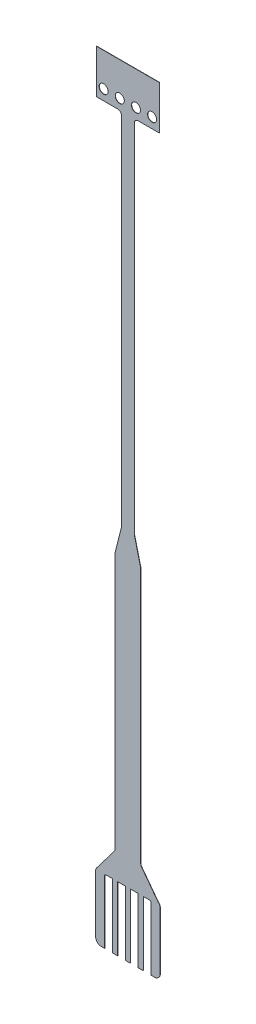
SolidWorks part; units mm, degrees
ref_plane "Front Plane" through (0, 0, 0) normal (0, 0, 1) x (1, 0, 0)
ref_plane "Top Plane" through (0, 0, 0) normal (0, 1, 0) x (1, 0, 0)
ref_plane "Right Plane" through (0, 0, 0) normal (1, 0, 0) x (0, 0, -1)
sketch "Model" plane through (0, 0, 0) normal (0, 0, 1) x (1, 0, 0)
  line L0 (-1.25, -28.292) -> (-1.2492, -28.3022)
  line L1 (-1.2492, -28.3022) -> (-1.2483, -28.3122)
  line L2 (-1.2483, -28.3122) -> (-1.2465, -28.3223)
  line L3 (-1.2465, -28.3223) -> (-1.2445, -28.332)
  line L4 (-1.2445, -28.332) -> (-1.242, -28.3417)
  line L5 (-1.242, -28.3417) -> (-1.239, -28.3515)
  line L6 (-1.239, -28.3515) -> (-1.2355, -28.361)
  line L7 (-1.2355, -28.361) -> (-1.2317, -28.3702)
  line L8 (-1.2317, -28.3702) -> (-1.2272, -28.3795)
  line L9 (-1.2272, -28.3795) -> (-1.2225, -28.3885)
  line L10 (-1.2225, -28.3885) -> (-1.2175, -28.397)
  line L11 (-1.2175, -28.397) -> (-1.2117, -28.4055)
  line L12 (-1.2117, -28.4055) -> (-1.206, -28.4135)
  line L13 (-1.206, -28.4135) -> (-1.1995, -28.4215)
  line L14 (-1.1995, -28.4215) -> (-1.1927, -28.429)
  line L15 (-1.1927, -28.429) -> (-1.1857, -28.4363)
  line L16 (-1.1857, -28.4363) -> (-1.1783, -28.443)
  line L17 (-1.1783, -28.443) -> (-1.1705, -28.4495)
  line L18 (-1.1705, -28.4495) -> (-1.1625, -28.4557)
  line L19 (-1.1625, -28.4557) -> (-1.1542, -28.4615)
  line L20 (-1.1542, -28.4615) -> (-1.1457, -28.4667)
  line L21 (-1.1457, -28.4667) -> (-1.137, -28.4717)
  line L22 (-1.137, -28.4717) -> (-1.1277, -28.4762)
  line L23 (-1.1277, -28.4762) -> (-1.1185, -28.4802)
  line L24 (-1.1185, -28.4802) -> (-1.1093, -28.484)
  line L25 (-1.1093, -28.484) -> (-1.0995, -28.4872)
  line L26 (-1.0995, -28.4872) -> (-1.09, -28.4897)
  line L27 (-1.09, -28.4897) -> (-1.08, -28.492)
  line L28 (-1.08, -28.492) -> (-1.07, -28.494)
  line L29 (-1.07, -28.494) -> (-1.06, -28.4952)
  line L30 (-1.06, -28.4952) -> (-1.05, -28.496)
  line L31 (-1.05, -28.496) -> (-0.9, -28.496)
  line L32 (-0.9, -28.496) -> (-0.9, -26.0412)
  line L33 (-0.9, -26.0412) -> (-0.8992, -26.0365)
  line L34 (-0.8992, -26.0365) -> (-0.8982, -26.0317)
  line L35 (-0.8982, -26.0317) -> (-0.8965, -26.027)
  line L36 (-0.8965, -26.027) -> (-0.8942, -26.0227)
  line L37 (-0.8942, -26.0227) -> (-0.8917, -26.0185)
  line L38 (-0.8917, -26.0185) -> (-0.889, -26.0145)
  line L39 (-0.889, -26.0145) -> (-0.8857, -26.0107)
  line L40 (-0.8857, -26.0107) -> (-0.882, -26.0075)
  line L41 (-0.882, -26.0075) -> (-0.878, -26.0048)
  line L42 (-0.878, -26.0048) -> (-0.8737, -26.0022)
  line L43 (-0.8737, -26.0022) -> (-0.8695, -26)
  line L44 (-0.8695, -26) -> (-0.8647, -25.9982)
  line L45 (-0.8647, -25.9982) -> (-0.86, -25.9973)
  line L46 (-0.86, -25.9973) -> (-0.8552, -25.9965)
  line L47 (-0.8552, -25.9965) -> (-0.8502, -25.9962)
  line L48 (-0.8502, -25.9962) -> (-0.8502, -25.996)
  line L49 (-0.8502, -25.996) -> (-0.605, -25.996)
  line L50 (-0.605, -25.996) -> (-0.6035, -25.9962)
  line L51 (-0.6035, -25.9962) -> (-0.602, -25.997)
  line L52 (-0.602, -25.997) -> (-0.601, -25.998)
  line L53 (-0.601, -25.998) -> (-0.6002, -25.9995)
  line L54 (-0.6002, -25.9995) -> (-0.6, -26.001)
  line L55 (-0.6, -26.001) -> (-0.6, -28.496)
  line L56 (-0.6, -28.496) -> (-0.4, -28.496)
  line L57 (-0.4, -28.496) -> (-0.4, -26.001)
  line L58 (-0.4, -26.001) -> (-0.3997, -25.9995)
  line L59 (-0.3997, -25.9995) -> (-0.399, -25.998)
  line L60 (-0.399, -25.998) -> (-0.398, -25.997)
  line L61 (-0.398, -25.997) -> (-0.3965, -25.9962)
  line L62 (-0.3965, -25.9962) -> (-0.395, -25.996)
  line L63 (-0.395, -25.996) -> (-0.105, -25.996)
  line L64 (-0.105, -25.996) -> (-0.1035, -25.9962)
  line L65 (-0.1035, -25.9962) -> (-0.102, -25.997)
  line L66 (-0.102, -25.997) -> (-0.101, -25.998)
  line L67 (-0.101, -25.998) -> (-0.1002, -25.9995)
  line L68 (-0.1002, -25.9995) -> (-0.1, -26.001)
  line L69 (-0.1, -26.001) -> (-0.1, -28.496)
  line L70 (-0.1, -28.496) -> (0.1, -28.496)
  line L71 (0.1, -28.496) -> (0.1, -26.001)
  line L72 (0.1, -26.001) -> (0.1002, -25.9995)
  line L73 (0.1002, -25.9995) -> (0.101, -25.998)
  line L74 (0.101, -25.998) -> (0.102, -25.997)
  line L75 (0.102, -25.997) -> (0.1035, -25.9962)
  line L76 (0.1035, -25.9962) -> (0.105, -25.996)
  line L77 (0.105, -25.996) -> (0.395, -25.996)
  line L78 (0.395, -25.996) -> (0.3965, -25.9962)
  line L79 (0.3965, -25.9962) -> (0.398, -25.997)
  line L80 (0.398, -25.997) -> (0.399, -25.998)
  line L81 (0.399, -25.998) -> (0.3997, -25.9995)
  line L82 (0.3997, -25.9995) -> (0.4, -26.001)
  line L83 (0.4, -26.001) -> (0.4, -28.496)
  line L84 (0.4, -28.496) -> (0.6, -28.496)
  line L85 (0.6, -28.496) -> (0.6, -26.001)
  line L86 (0.6, -26.001) -> (0.6002, -25.9995)
  line L87 (0.6002, -25.9995) -> (0.601, -25.998)
  line L88 (0.601, -25.998) -> (0.602, -25.997)
  line L89 (0.602, -25.997) -> (0.6035, -25.9962)
  line L90 (0.6035, -25.9962) -> (0.605, -25.996)
  line L91 (0.605, -25.996) -> (0.85, -25.996)
  line L92 (0.85, -25.996) -> (0.855, -25.9962)
  line L93 (0.855, -25.9962) -> (0.8597, -25.997)
  line L94 (0.8597, -25.997) -> (0.8645, -25.998)
  line L95 (0.8645, -25.998) -> (0.8692, -25.9997)
  line L96 (0.8692, -25.9997) -> (0.8735, -26.002)
  line L97 (0.8735, -26.002) -> (0.8777, -26.0045)
  line L98 (0.8777, -26.0045) -> (0.8817, -26.0072)
  line L99 (0.8817, -26.0072) -> (0.8855, -26.0105)
  line L100 (0.8855, -26.0105) -> (0.8888, -26.0143)
  line L101 (0.8888, -26.0143) -> (0.8915, -26.0182)
  line L102 (0.8915, -26.0182) -> (0.894, -26.0225)
  line L103 (0.894, -26.0225) -> (0.8962, -26.0267)
  line L104 (0.8962, -26.0267) -> (0.898, -26.0315)
  line L105 (0.898, -26.0315) -> (0.899, -26.0362)
  line L106 (0.899, -26.0362) -> (0.8997, -26.041)
  line L107 (0.8997, -26.041) -> (0.9, -26.046)
  line L108 (0.9, -26.046) -> (0.9, -28.496)
  line L109 (0.9, -28.496) -> (1.05, -28.496)
  line L110 (1.05, -28.496) -> (1.06, -28.4952)
  line L111 (1.06, -28.4952) -> (1.07, -28.494)
  line L112 (1.07, -28.494) -> (1.08, -28.492)
  line L113 (1.08, -28.492) -> (1.0897, -28.4897)
  line L114 (1.0897, -28.4897) -> (1.0995, -28.4872)
  line L115 (1.0995, -28.4872) -> (1.1093, -28.484)
  line L116 (1.1093, -28.484) -> (1.1185, -28.4802)
  line L117 (1.1185, -28.4802) -> (1.1277, -28.4762)
  line L118 (1.1277, -28.4762) -> (1.137, -28.4717)
  line L119 (1.137, -28.4717) -> (1.1457, -28.4667)
  line L120 (1.1457, -28.4667) -> (1.1542, -28.4615)
  line L121 (1.1542, -28.4615) -> (1.1625, -28.4557)
  line L122 (1.1625, -28.4557) -> (1.1705, -28.4495)
  line L123 (1.1705, -28.4495) -> (1.1783, -28.443)
  line L124 (1.1783, -28.443) -> (1.1857, -28.4363)
  line L125 (1.1857, -28.4363) -> (1.1927, -28.429)
  line L126 (1.1927, -28.429) -> (1.1995, -28.4215)
  line L127 (1.1995, -28.4215) -> (1.206, -28.4137)
  line L128 (1.206, -28.4137) -> (1.2117, -28.4055)
  line L129 (1.2117, -28.4055) -> (1.2175, -28.397)
  line L130 (1.2175, -28.397) -> (1.2225, -28.3885)
  line L131 (1.2225, -28.3885) -> (1.2272, -28.3795)
  line L132 (1.2272, -28.3795) -> (1.2317, -28.3702)
  line L133 (1.2317, -28.3702) -> (1.2355, -28.361)
  line L134 (1.2355, -28.361) -> (1.239, -28.3515)
  line L135 (1.239, -28.3515) -> (1.242, -28.3417)
  line L136 (1.242, -28.3417) -> (1.2445, -28.332)
  line L137 (1.2445, -28.332) -> (1.2465, -28.3223)
  line L138 (1.2465, -28.3223) -> (1.2483, -28.3122)
  line L139 (1.2483, -28.3122) -> (1.2492, -28.3022)
  line L140 (1.2492, -28.3022) -> (1.25, -28.292)
  line L141 (1.25, -28.292) -> (1.25, -26.046)
  line L142 (1.25, -26.046) -> (1.25, -26.045)
  line L143 (1.25, -26.045) -> (1.2497, -26.037)
  line L144 (1.2497, -26.037) -> (1.249, -26.028)
  line L145 (1.249, -26.028) -> (1.248, -26.019)
  line L146 (1.248, -26.019) -> (1.2462, -26.01)
  line L147 (1.2462, -26.01) -> (1.2442, -26.0012)
  line L148 (1.2442, -26.0012) -> (1.2417, -25.9925)
  line L149 (1.2417, -25.9925) -> (1.2388, -25.984)
  line L150 (1.2388, -25.984) -> (1.2352, -25.9757)
  line L151 (1.2352, -25.9757) -> (1.2315, -25.9675)
  line L152 (1.2315, -25.9675) -> (1.227, -25.9595)
  line L153 (1.227, -25.9595) -> (1.2225, -25.9518)
  line L154 (1.2225, -25.9518) -> (1.2172, -25.9443)
  line L155 (1.2172, -25.9443) -> (1.212, -25.937)
  line L156 (1.212, -25.937) -> (1.206, -25.93)
  line L157 (1.206, -25.93) -> (1.2, -25.9235)
  line L158 (1.2, -25.9235) -> (1.1935, -25.9172)
  line L159 (1.1935, -25.9172) -> (1.1865, -25.9112)
  line L160 (1.1865, -25.9112) -> (1.1863, -25.9111)
  line L161 (1.1863, -25.9111) -> (0.522, -25.0253)
  line L162 (0.522, -25.0253) -> (0.521, -25.0237)
  line L163 (0.521, -25.0237) -> (0.517, -25.0167)
  line L164 (0.517, -25.0167) -> (0.5135, -25.0095)
  line L165 (0.5135, -25.0095) -> (0.5102, -25.002)
  line L166 (0.5102, -25.002) -> (0.5075, -24.9945)
  line L167 (0.5075, -24.9945) -> (0.5052, -24.9867)
  line L168 (0.5052, -24.9867) -> (0.5032, -24.979)
  line L169 (0.5032, -24.979) -> (0.5018, -24.971)
  line L170 (0.5018, -24.971) -> (0.5008, -24.963)
  line L171 (0.5008, -24.963) -> (0.5, -24.955)
  line L172 (0.5, -24.955) -> (0.5, -14.996)
  line L173 (0.5, -14.996) -> (0.25, -13.996)
  line L174 (-0.25, -13.996) -> (-0.25, -0.15)
  line L175 (0.25, -13.996) -> (0.25, -0.15)
  line L177 (-0.25, -13.996) -> (-0.5, -14.996)
  line L178 (-0.5, -14.996) -> (-0.5, -24.948)
  line L179 (-0.5, -24.948) -> (-0.5002, -24.956)
  line L180 (-0.5002, -24.956) -> (-0.5008, -24.964)
  line L181 (-0.5008, -24.964) -> (-0.502, -24.972)
  line L182 (-0.502, -24.972) -> (-0.5035, -24.98)
  line L183 (-0.5035, -24.98) -> (-0.5052, -24.9877)
  line L184 (-0.5052, -24.9877) -> (-0.5077, -24.9955)
  line L185 (-0.5077, -24.9955) -> (-0.5105, -25.003)
  line L186 (-0.5105, -25.003) -> (-0.5135, -25.0105)
  line L187 (-0.5135, -25.0105) -> (-0.5172, -25.0177)
  line L188 (-0.5172, -25.0177) -> (-0.5196, -25.0221)
  line L189 (-0.5196, -25.0221) -> (-1.1864, -25.9113)
  line L190 (-1.1864, -25.9113) -> (-1.1867, -25.9115)
  line L191 (-1.1867, -25.9115) -> (-1.1935, -25.9175)
  line L192 (-1.1935, -25.9175) -> (-1.2, -25.9237)
  line L193 (-1.2, -25.9237) -> (-1.2062, -25.9302)
  line L194 (-1.2062, -25.9302) -> (-1.212, -25.9372)
  line L195 (-1.212, -25.9372) -> (-1.2175, -25.9445)
  line L196 (-1.2175, -25.9445) -> (-1.2225, -25.952)
  line L197 (-1.2225, -25.952) -> (-1.2272, -25.9597)
  line L198 (-1.2272, -25.9597) -> (-1.2315, -25.9677)
  line L199 (-1.2315, -25.9677) -> (-1.2352, -25.976)
  line L200 (-1.2352, -25.976) -> (-1.2388, -25.9842)
  line L201 (-1.2388, -25.9842) -> (-1.2417, -25.9927)
  line L202 (-1.2417, -25.9927) -> (-1.2442, -26.0015)
  line L203 (-1.2442, -26.0015) -> (-1.2462, -26.0102)
  line L204 (-1.2462, -26.0102) -> (-1.248, -26.0192)
  line L205 (-1.248, -26.0192) -> (-1.249, -26.0282)
  line L206 (-1.249, -26.0282) -> (-1.2497, -26.0372)
  line L207 (-1.2497, -26.0372) -> (-1.25, -26.0457)
  line L208 (-1.25, -26.0457) -> (-1.25, -26.046)
  line L209 (-1.25, -26.046) -> (-1.25, -28.292)
  line L210 (-1.225, 0) -> (-0.4, 0)
  line L211 (-0.4, 0) -> (-0.3915, -0.0003)
  line L212 (-0.3915, -0.0003) -> (-0.3832, -0.001)
  line L213 (-0.3832, -0.001) -> (-0.3747, -0.002)
  line L214 (-0.3747, -0.002) -> (-0.3665, -0.0037)
  line L215 (-0.3665, -0.0037) -> (-0.3585, -0.0057)
  line L216 (-0.3585, -0.0057) -> (-0.3505, -0.0085)
  line L217 (-0.3505, -0.0085) -> (-0.3425, -0.0115)
  line L218 (-0.3425, -0.0115) -> (-0.335, -0.0147)
  line L219 (-0.335, -0.0147) -> (-0.3275, -0.0187)
  line L220 (-0.3275, -0.0187) -> (-0.3202, -0.023)
  line L221 (-0.3202, -0.023) -> (-0.3132, -0.0278)
  line L222 (-0.3132, -0.0278) -> (-0.3065, -0.0327)
  line L223 (-0.3065, -0.0327) -> (-0.3, -0.0382)
  line L224 (-0.3, -0.0382) -> (-0.294, -0.044)
  line L225 (-0.294, -0.044) -> (-0.2883, -0.05)
  line L226 (-0.2883, -0.05) -> (-0.2827, -0.0565)
  line L227 (-0.2827, -0.0565) -> (-0.2777, -0.0632)
  line L228 (-0.2777, -0.0632) -> (-0.273, -0.0703)
  line L229 (-0.273, -0.0703) -> (-0.2687, -0.0775)
  line L230 (-0.2687, -0.0775) -> (-0.2647, -0.085)
  line L231 (-0.2647, -0.085) -> (-0.2615, -0.0925)
  line L232 (-0.2615, -0.0925) -> (-0.2585, -0.1005)
  line L233 (-0.2585, -0.1005) -> (-0.2558, -0.1085)
  line L234 (-0.2558, -0.1085) -> (-0.2538, -0.1165)
  line L235 (-0.2538, -0.1165) -> (-0.252, -0.1247)
  line L236 (-0.252, -0.1247) -> (-0.251, -0.1332)
  line L237 (-0.251, -0.1332) -> (-0.2502, -0.1415)
  line L238 (-0.2502, -0.1415) -> (-0.25, -0.15)
  line L239 (1.225, 0) -> (1.225, 1.7)
  line L276 (0.25, -0.15) -> (0.2502, -0.1415)
  line L277 (0.2502, -0.1415) -> (0.251, -0.1332)
  line L278 (0.251, -0.1332) -> (0.252, -0.1247)
  line L279 (0.252, -0.1247) -> (0.2538, -0.1165)
  line L280 (0.2538, -0.1165) -> (0.2558, -0.1085)
  line L281 (0.2558, -0.1085) -> (0.2585, -0.1005)
  line L282 (0.2585, -0.1005) -> (0.2615, -0.0925)
  line L283 (0.2615, -0.0925) -> (0.2647, -0.085)
  line L284 (0.2647, -0.085) -> (0.2687, -0.0775)
  line L285 (0.2687, -0.0775) -> (0.273, -0.0703)
  line L286 (0.273, -0.0703) -> (0.2777, -0.0632)
  line L287 (0.2777, -0.0632) -> (0.2827, -0.0565)
  line L288 (0.2827, -0.0565) -> (0.2883, -0.05)
  line L289 (0.2883, -0.05) -> (0.294, -0.044)
  line L290 (0.294, -0.044) -> (0.3, -0.0382)
  line L291 (0.3, -0.0382) -> (0.3065, -0.0327)
  line L292 (0.3065, -0.0327) -> (0.3132, -0.0278)
  line L293 (0.3132, -0.0278) -> (0.3202, -0.023)
  line L294 (0.3202, -0.023) -> (0.3275, -0.0187)
  line L295 (0.3275, -0.0187) -> (0.335, -0.0147)
  line L296 (0.335, -0.0147) -> (0.3425, -0.0115)
  line L297 (0.3425, -0.0115) -> (0.3505, -0.0085)
  line L298 (0.3505, -0.0085) -> (0.3585, -0.0057)
  line L299 (0.3585, -0.0057) -> (0.3665, -0.0037)
  line L300 (0.3665, -0.0037) -> (0.3747, -0.002)
  line L301 (0.3747, -0.002) -> (0.3832, -0.001)
  line L302 (0.3832, -0.001) -> (0.3915, -0.0003)
  line L303 (0.3915, -0.0003) -> (0.4, 0)
  line L304 (0.4, 0) -> (1.225, 0)
  line L442 (1.225, 1.7) -> (0.767, 1.7)
  line L444 (0.767, 0.4) -> (0.7672, 0.4068)
  line L445 (0.7672, 0.4068) -> (0.7675, 0.413)
  line L446 (0.7675, 0.413) -> (0.7682, 0.4197)
  line L447 (0.7682, 0.4197) -> (0.769, 0.4262)
  line L448 (0.769, 0.4262) -> (0.7702, 0.4327)
  line L449 (0.7702, 0.4327) -> (0.7715, 0.439)
  line L450 (0.7715, 0.439) -> (0.773, 0.4452)
  line L451 (0.773, 0.4452) -> (0.7747, 0.4515)
  line L452 (0.7747, 0.4515) -> (0.777, 0.458)
  line L453 (0.777, 0.458) -> (0.7792, 0.464)
  line L454 (0.7792, 0.464) -> (0.7818, 0.47)
  line L455 (0.7818, 0.47) -> (0.7843, 0.4758)
  line L456 (0.7843, 0.4758) -> (0.7875, 0.482)
  line L457 (0.7875, 0.482) -> (0.7905, 0.4875)
  line L458 (0.7905, 0.4875) -> (0.794, 0.4932)
  line L459 (0.794, 0.4932) -> (0.7975, 0.4985)
  line L460 (0.7975, 0.4985) -> (0.8013, 0.5037)
  line L461 (0.8013, 0.5037) -> (0.8053, 0.509)
  line L462 (0.8053, 0.509) -> (0.8092, 0.514)
  line L463 (0.8092, 0.514) -> (0.8137, 0.519)
  line L464 (0.8137, 0.519) -> (0.823, 0.5282)
  line L465 (0.823, 0.5282) -> (0.828, 0.5328)
  line L466 (0.828, 0.5328) -> (0.833, 0.5368)
  line L467 (0.833, 0.5368) -> (0.8382, 0.5407)
  line L468 (0.8382, 0.5407) -> (0.8435, 0.5445)
  line L469 (0.8435, 0.5445) -> (0.8488, 0.548)
  line L470 (0.8488, 0.548) -> (0.8545, 0.5515)
  line L471 (0.8545, 0.5515) -> (0.86, 0.5545)
  line L472 (0.86, 0.5545) -> (0.8662, 0.5577)
  line L473 (0.8662, 0.5577) -> (0.872, 0.5603)
  line L474 (0.872, 0.5603) -> (0.878, 0.5627)
  line L475 (0.878, 0.5627) -> (0.884, 0.565)
  line L476 (0.884, 0.565) -> (0.8905, 0.5672)
  line L477 (0.8905, 0.5672) -> (0.8967, 0.569)
  line L478 (0.8967, 0.569) -> (0.903, 0.5705)
  line L479 (0.903, 0.5705) -> (0.9093, 0.5717)
  line L480 (0.9093, 0.5717) -> (0.9157, 0.573)
  line L481 (0.9157, 0.573) -> (0.9223, 0.5737)
  line L482 (0.9223, 0.5737) -> (0.929, 0.5745)
  line L483 (0.929, 0.5745) -> (0.9353, 0.5747)
  line L484 (0.9353, 0.5747) -> (0.942, 0.575)
  line L485 (0.942, 0.575) -> (0.9487, 0.5747)
  line L486 (0.9487, 0.5747) -> (0.955, 0.5745)
  line L487 (0.955, 0.5745) -> (0.9617, 0.5737)
  line L488 (0.9617, 0.5737) -> (0.9682, 0.573)
  line L489 (0.9682, 0.573) -> (0.9747, 0.5717)
  line L490 (0.9747, 0.5717) -> (0.981, 0.5705)
  line L491 (0.981, 0.5705) -> (0.9873, 0.569)
  line L492 (0.9873, 0.569) -> (0.9935, 0.5672)
  line L493 (0.9935, 0.5672) -> (1, 0.565)
  line L494 (1, 0.565) -> (1.006, 0.5627)
  line L495 (1.006, 0.5627) -> (1.012, 0.5603)
  line L496 (1.012, 0.5603) -> (1.0177, 0.5577)
  line L497 (1.0177, 0.5577) -> (1.024, 0.5545)
  line L498 (1.024, 0.5545) -> (1.0295, 0.5515)
  line L499 (1.0295, 0.5515) -> (1.0353, 0.548)
  line L500 (1.0353, 0.548) -> (1.0405, 0.5445)
  line L501 (1.0405, 0.5445) -> (1.0457, 0.5407)
  line L502 (1.0457, 0.5407) -> (1.051, 0.5368)
  line L503 (1.051, 0.5368) -> (1.056, 0.5328)
  line L504 (1.056, 0.5328) -> (1.061, 0.5282)
  line L505 (1.061, 0.5282) -> (1.0702, 0.519)
  line L506 (1.0702, 0.519) -> (1.0747, 0.514)
  line L507 (1.0747, 0.514) -> (1.0787, 0.509)
  line L508 (1.0787, 0.509) -> (1.0827, 0.5037)
  line L509 (1.0827, 0.5037) -> (1.0865, 0.4985)
  line L510 (1.0865, 0.4985) -> (1.09, 0.4932)
  line L511 (1.09, 0.4932) -> (1.0935, 0.4875)
  line L512 (1.0935, 0.4875) -> (1.0965, 0.482)
  line L513 (1.0965, 0.482) -> (1.0998, 0.4758)
  line L514 (1.0998, 0.4758) -> (1.1022, 0.47)
  line L515 (1.1022, 0.47) -> (1.1048, 0.464)
  line L516 (1.1048, 0.464) -> (1.107, 0.458)
  line L517 (1.107, 0.458) -> (1.1093, 0.4515)
  line L518 (1.1093, 0.4515) -> (1.111, 0.4452)
  line L519 (1.111, 0.4452) -> (1.1125, 0.439)
  line L520 (1.1125, 0.439) -> (1.1138, 0.4327)
  line L521 (1.1138, 0.4327) -> (1.115, 0.4262)
  line L522 (1.115, 0.4262) -> (1.1158, 0.4197)
  line L523 (1.1158, 0.4197) -> (1.1165, 0.413)
  line L524 (1.1165, 0.413) -> (1.1167, 0.4068)
  line L525 (1.1167, 0.4068) -> (1.117, 0.4)
  line L526 (1.117, 0.4) -> (1.1167, 0.3932)
  line L527 (1.1167, 0.3932) -> (1.1165, 0.387)
  line L528 (1.1165, 0.387) -> (1.1158, 0.3802)
  line L529 (1.1158, 0.3802) -> (1.115, 0.3738)
  line L530 (1.115, 0.3738) -> (1.1138, 0.3673)
  line L531 (1.1138, 0.3673) -> (1.1125, 0.361)
  line L532 (1.1125, 0.361) -> (1.111, 0.3547)
  line L533 (1.111, 0.3547) -> (1.1093, 0.3485)
  line L534 (1.1093, 0.3485) -> (1.107, 0.342)
  line L535 (1.107, 0.342) -> (1.1048, 0.336)
  line L536 (1.1048, 0.336) -> (1.1022, 0.33)
  line L537 (1.1022, 0.33) -> (1.0998, 0.3242)
  line L538 (1.0998, 0.3242) -> (1.0965, 0.318)
  line L539 (1.0965, 0.318) -> (1.0935, 0.3125)
  line L540 (1.0935, 0.3125) -> (1.09, 0.3068)
  line L541 (1.09, 0.3068) -> (1.0865, 0.3015)
  line L542 (1.0865, 0.3015) -> (1.0827, 0.2962)
  line L543 (1.0827, 0.2962) -> (1.0787, 0.291)
  line L544 (1.0787, 0.291) -> (1.0747, 0.286)
  line L545 (1.0747, 0.286) -> (1.0702, 0.281)
  line L546 (1.0702, 0.281) -> (1.061, 0.2717)
  line L547 (1.061, 0.2717) -> (1.056, 0.2672)
  line L548 (1.056, 0.2672) -> (1.051, 0.2632)
  line L549 (1.051, 0.2632) -> (1.0457, 0.2592)
  line L550 (1.0457, 0.2592) -> (1.0405, 0.2555)
  line L551 (1.0405, 0.2555) -> (1.0353, 0.252)
  line L552 (1.0353, 0.252) -> (1.0295, 0.2485)
  line L553 (1.0295, 0.2485) -> (1.024, 0.2455)
  line L554 (1.024, 0.2455) -> (1.0177, 0.2422)
  line L555 (1.0177, 0.2422) -> (1.012, 0.2397)
  line L556 (1.012, 0.2397) -> (1.006, 0.2372)
  line L557 (1.006, 0.2372) -> (1, 0.235)
  line L558 (1, 0.235) -> (0.9935, 0.2327)
  line L559 (0.9935, 0.2327) -> (0.9873, 0.231)
  line L560 (0.9873, 0.231) -> (0.981, 0.2295)
  line L561 (0.981, 0.2295) -> (0.9747, 0.2282)
  line L562 (0.9747, 0.2282) -> (0.9682, 0.227)
  line L563 (0.9682, 0.227) -> (0.9617, 0.2263)
  line L564 (0.9617, 0.2263) -> (0.955, 0.2255)
  line L565 (0.955, 0.2255) -> (0.9487, 0.2253)
  line L566 (0.9487, 0.2253) -> (0.942, 0.225)
  line L567 (0.942, 0.225) -> (0.9353, 0.2253)
  line L568 (0.9353, 0.2253) -> (0.929, 0.2255)
  line L569 (0.929, 0.2255) -> (0.9223, 0.2263)
  line L570 (0.9223, 0.2263) -> (0.9157, 0.227)
  line L571 (0.9157, 0.227) -> (0.9093, 0.2282)
  line L572 (0.9093, 0.2282) -> (0.903, 0.2295)
  line L573 (0.903, 0.2295) -> (0.8967, 0.231)
  line L574 (0.8967, 0.231) -> (0.8905, 0.2327)
  line L575 (0.8905, 0.2327) -> (0.884, 0.235)
  line L576 (0.884, 0.235) -> (0.878, 0.2372)
  line L577 (0.878, 0.2372) -> (0.872, 0.2397)
  line L578 (0.872, 0.2397) -> (0.8662, 0.2422)
  line L579 (0.8662, 0.2422) -> (0.86, 0.2455)
  line L580 (0.86, 0.2455) -> (0.8545, 0.2485)
  line L581 (0.8545, 0.2485) -> (0.8488, 0.252)
  line L582 (0.8488, 0.252) -> (0.8435, 0.2555)
  line L583 (0.8435, 0.2555) -> (0.8382, 0.2592)
  line L584 (0.8382, 0.2592) -> (0.833, 0.2632)
  line L585 (0.833, 0.2632) -> (0.828, 0.2672)
  line L586 (0.828, 0.2672) -> (0.823, 0.2717)
  line L587 (0.823, 0.2717) -> (0.8137, 0.281)
  line L588 (0.8137, 0.281) -> (0.8092, 0.286)
  line L589 (0.8092, 0.286) -> (0.8053, 0.291)
  line L590 (0.8053, 0.291) -> (0.8013, 0.2962)
  line L591 (0.8013, 0.2962) -> (0.7975, 0.3015)
  line L592 (0.7975, 0.3015) -> (0.794, 0.3068)
  line L593 (0.794, 0.3068) -> (0.7905, 0.3125)
  line L594 (0.7905, 0.3125) -> (0.7875, 0.318)
  line L595 (0.7875, 0.318) -> (0.7843, 0.3242)
  line L596 (0.7843, 0.3242) -> (0.7818, 0.33)
  line L597 (0.7818, 0.33) -> (0.7792, 0.336)
  line L598 (0.7792, 0.336) -> (0.777, 0.342)
  line L599 (0.777, 0.342) -> (0.7747, 0.3485)
  line L600 (0.7747, 0.3485) -> (0.773, 0.3547)
  line L601 (0.773, 0.3547) -> (0.7715, 0.361)
  line L602 (0.7715, 0.361) -> (0.7702, 0.3673)
  line L603 (0.7702, 0.3673) -> (0.769, 0.3738)
  line L604 (0.769, 0.3738) -> (0.7682, 0.3802)
  line L605 (0.7682, 0.3802) -> (0.7675, 0.387)
  line L606 (0.7675, 0.387) -> (0.7672, 0.3932)
  line L607 (0.7672, 0.3932) -> (0.767, 0.4)
  line L609 (0.767, 1.7) -> (0.139, 1.7)
  line L611 (0.139, 0.4) -> (0.1392, 0.4068)
  line L612 (0.1392, 0.4068) -> (0.1395, 0.413)
  line L613 (0.1395, 0.413) -> (0.1402, 0.4197)
  line L614 (0.1402, 0.4197) -> (0.141, 0.4262)
  line L615 (0.141, 0.4262) -> (0.1422, 0.4327)
  line L616 (0.1422, 0.4327) -> (0.1435, 0.439)
  line L617 (0.1435, 0.439) -> (0.145, 0.4452)
  line L618 (0.145, 0.4452) -> (0.1467, 0.4515)
  line L619 (0.1467, 0.4515) -> (0.149, 0.458)
  line L620 (0.149, 0.458) -> (0.1512, 0.464)
  line L621 (0.1512, 0.464) -> (0.1537, 0.47)
  line L622 (0.1537, 0.47) -> (0.1562, 0.4758)
  line L623 (0.1562, 0.4758) -> (0.1595, 0.482)
  line L624 (0.1595, 0.482) -> (0.1625, 0.4875)
  line L625 (0.1625, 0.4875) -> (0.166, 0.4932)
  line L626 (0.166, 0.4932) -> (0.1695, 0.4985)
  line L627 (0.1695, 0.4985) -> (0.1732, 0.5037)
  line L628 (0.1732, 0.5037) -> (0.1772, 0.509)
  line L629 (0.1772, 0.509) -> (0.1812, 0.514)
  line L630 (0.1812, 0.514) -> (0.1857, 0.519)
  line L631 (0.1857, 0.519) -> (0.195, 0.5282)
  line L632 (0.195, 0.5282) -> (0.2, 0.5328)
  line L633 (0.2, 0.5328) -> (0.205, 0.5368)
  line L634 (0.205, 0.5368) -> (0.2102, 0.5407)
  line L635 (0.2102, 0.5407) -> (0.2155, 0.5445)
  line L636 (0.2155, 0.5445) -> (0.2208, 0.548)
  line L637 (0.2208, 0.548) -> (0.2265, 0.5515)
  line L638 (0.2265, 0.5515) -> (0.232, 0.5545)
  line L639 (0.232, 0.5545) -> (0.2382, 0.5577)
  line L640 (0.2382, 0.5577) -> (0.244, 0.5603)
  line L641 (0.244, 0.5603) -> (0.25, 0.5627)
  line L642 (0.25, 0.5627) -> (0.256, 0.565)
  line L643 (0.256, 0.565) -> (0.2625, 0.5672)
  line L644 (0.2625, 0.5672) -> (0.2687, 0.569)
  line L645 (0.2687, 0.569) -> (0.275, 0.5705)
  line L646 (0.275, 0.5705) -> (0.2812, 0.5717)
  line L647 (0.2812, 0.5717) -> (0.2877, 0.573)
  line L648 (0.2877, 0.573) -> (0.2942, 0.5737)
  line L649 (0.2942, 0.5737) -> (0.301, 0.5745)
  line L650 (0.301, 0.5745) -> (0.3072, 0.5747)
  line L651 (0.3072, 0.5747) -> (0.314, 0.575)
  line L652 (0.314, 0.575) -> (0.3207, 0.5747)
  line L653 (0.3207, 0.5747) -> (0.327, 0.5745)
  line L654 (0.327, 0.5745) -> (0.3337, 0.5737)
  line L655 (0.3337, 0.5737) -> (0.3402, 0.573)
  line L656 (0.3402, 0.573) -> (0.3468, 0.5717)
  line L657 (0.3468, 0.5717) -> (0.353, 0.5705)
  line L658 (0.353, 0.5705) -> (0.3592, 0.569)
  line L659 (0.3592, 0.569) -> (0.3655, 0.5672)
  line L660 (0.3655, 0.5672) -> (0.372, 0.565)
  line L661 (0.372, 0.565) -> (0.378, 0.5627)
  line L662 (0.378, 0.5627) -> (0.384, 0.5603)
  line L663 (0.384, 0.5603) -> (0.3897, 0.5577)
  line L664 (0.3897, 0.5577) -> (0.396, 0.5545)
  line L665 (0.396, 0.5545) -> (0.4015, 0.5515)
  line L666 (0.4015, 0.5515) -> (0.4073, 0.548)
  line L667 (0.4073, 0.548) -> (0.4125, 0.5445)
  line L668 (0.4125, 0.5445) -> (0.4178, 0.5407)
  line L669 (0.4178, 0.5407) -> (0.423, 0.5368)
  line L670 (0.423, 0.5368) -> (0.428, 0.5328)
  line L671 (0.428, 0.5328) -> (0.433, 0.5282)
  line L672 (0.433, 0.5282) -> (0.4422, 0.519)
  line L673 (0.4422, 0.519) -> (0.4467, 0.514)
  line L674 (0.4467, 0.514) -> (0.4507, 0.509)
  line L675 (0.4507, 0.509) -> (0.4547, 0.5037)
  line L676 (0.4547, 0.5037) -> (0.4585, 0.4985)
  line L677 (0.4585, 0.4985) -> (0.462, 0.4932)
  line L678 (0.462, 0.4932) -> (0.4655, 0.4875)
  line L679 (0.4655, 0.4875) -> (0.4685, 0.482)
  line L680 (0.4685, 0.482) -> (0.4718, 0.4758)
  line L681 (0.4718, 0.4758) -> (0.4742, 0.47)
  line L682 (0.4742, 0.47) -> (0.4767, 0.464)
  line L683 (0.4767, 0.464) -> (0.479, 0.458)
  line L684 (0.479, 0.458) -> (0.4812, 0.4515)
  line L685 (0.4812, 0.4515) -> (0.483, 0.4452)
  line L686 (0.483, 0.4452) -> (0.4845, 0.439)
  line L687 (0.4845, 0.439) -> (0.4857, 0.4327)
  line L688 (0.4857, 0.4327) -> (0.487, 0.4262)
  line L689 (0.487, 0.4262) -> (0.4877, 0.4197)
  line L690 (0.4877, 0.4197) -> (0.4885, 0.413)
  line L691 (0.4885, 0.413) -> (0.4887, 0.4068)
  line L692 (0.4887, 0.4068) -> (0.489, 0.4)
  line L693 (0.489, 0.4) -> (0.4887, 0.3932)
  line L694 (0.4887, 0.3932) -> (0.4885, 0.387)
  line L695 (0.4885, 0.387) -> (0.4877, 0.3802)
  line L696 (0.4877, 0.3802) -> (0.487, 0.3738)
  line L697 (0.487, 0.3738) -> (0.4857, 0.3673)
  line L698 (0.4857, 0.3673) -> (0.4845, 0.361)
  line L699 (0.4845, 0.361) -> (0.483, 0.3547)
  line L700 (0.483, 0.3547) -> (0.4812, 0.3485)
  line L701 (0.4812, 0.3485) -> (0.479, 0.342)
  line L702 (0.479, 0.342) -> (0.4767, 0.336)
  line L703 (0.4767, 0.336) -> (0.4742, 0.33)
  line L704 (0.4742, 0.33) -> (0.4718, 0.3242)
  line L705 (0.4718, 0.3242) -> (0.4685, 0.318)
  line L706 (0.4685, 0.318) -> (0.4655, 0.3125)
  line L707 (0.4655, 0.3125) -> (0.462, 0.3068)
  line L708 (0.462, 0.3068) -> (0.4585, 0.3015)
  line L709 (0.4585, 0.3015) -> (0.4547, 0.2962)
  line L710 (0.4547, 0.2962) -> (0.4507, 0.291)
  line L711 (0.4507, 0.291) -> (0.4467, 0.286)
  line L712 (0.4467, 0.286) -> (0.4422, 0.281)
  line L713 (0.4422, 0.281) -> (0.433, 0.2717)
  line L714 (0.433, 0.2717) -> (0.428, 0.2672)
  line L715 (0.428, 0.2672) -> (0.423, 0.2632)
  line L716 (0.423, 0.2632) -> (0.4178, 0.2592)
  line L717 (0.4178, 0.2592) -> (0.4125, 0.2555)
  line L718 (0.4125, 0.2555) -> (0.4073, 0.252)
  line L719 (0.4073, 0.252) -> (0.4015, 0.2485)
  line L720 (0.4015, 0.2485) -> (0.396, 0.2455)
  line L721 (0.396, 0.2455) -> (0.3897, 0.2422)
  line L722 (0.3897, 0.2422) -> (0.384, 0.2397)
  line L723 (0.384, 0.2397) -> (0.378, 0.2372)
  line L724 (0.378, 0.2372) -> (0.372, 0.235)
  line L725 (0.372, 0.235) -> (0.3655, 0.2327)
  line L726 (0.3655, 0.2327) -> (0.3592, 0.231)
  line L727 (0.3592, 0.231) -> (0.353, 0.2295)
  line L728 (0.353, 0.2295) -> (0.3468, 0.2282)
  line L729 (0.3468, 0.2282) -> (0.3402, 0.227)
  line L730 (0.3402, 0.227) -> (0.3337, 0.2263)
  line L731 (0.3337, 0.2263) -> (0.327, 0.2255)
  line L732 (0.327, 0.2255) -> (0.3207, 0.2253)
  line L733 (0.3207, 0.2253) -> (0.314, 0.225)
  line L734 (0.314, 0.225) -> (0.3072, 0.2253)
  line L735 (0.3072, 0.2253) -> (0.301, 0.2255)
  line L736 (0.301, 0.2255) -> (0.2942, 0.2263)
  line L737 (0.2942, 0.2263) -> (0.2877, 0.227)
  line L738 (0.2877, 0.227) -> (0.2812, 0.2282)
  line L739 (0.2812, 0.2282) -> (0.275, 0.2295)
  line L740 (0.275, 0.2295) -> (0.2687, 0.231)
  line L741 (0.2687, 0.231) -> (0.2625, 0.2327)
  line L742 (0.2625, 0.2327) -> (0.256, 0.235)
  line L743 (0.256, 0.235) -> (0.25, 0.2372)
  line L744 (0.25, 0.2372) -> (0.244, 0.2397)
  line L745 (0.244, 0.2397) -> (0.2382, 0.2422)
  line L746 (0.2382, 0.2422) -> (0.232, 0.2455)
  line L747 (0.232, 0.2455) -> (0.2265, 0.2485)
  line L748 (0.2265, 0.2485) -> (0.2208, 0.252)
  line L749 (0.2208, 0.252) -> (0.2155, 0.2555)
  line L750 (0.2155, 0.2555) -> (0.2102, 0.2592)
  line L751 (0.2102, 0.2592) -> (0.205, 0.2632)
  line L752 (0.205, 0.2632) -> (0.2, 0.2672)
  line L753 (0.2, 0.2672) -> (0.195, 0.2717)
  line L754 (0.195, 0.2717) -> (0.1857, 0.281)
  line L755 (0.1857, 0.281) -> (0.1812, 0.286)
  line L756 (0.1812, 0.286) -> (0.1772, 0.291)
  line L757 (0.1772, 0.291) -> (0.1732, 0.2962)
  line L758 (0.1732, 0.2962) -> (0.1695, 0.3015)
  line L759 (0.1695, 0.3015) -> (0.166, 0.3068)
  line L760 (0.166, 0.3068) -> (0.1625, 0.3125)
  line L761 (0.1625, 0.3125) -> (0.1595, 0.318)
  line L762 (0.1595, 0.318) -> (0.1562, 0.3242)
  line L763 (0.1562, 0.3242) -> (0.1537, 0.33)
  line L764 (0.1537, 0.33) -> (0.1512, 0.336)
  line L765 (0.1512, 0.336) -> (0.149, 0.342)
  line L766 (0.149, 0.342) -> (0.1467, 0.3485)
  line L767 (0.1467, 0.3485) -> (0.145, 0.3547)
  line L768 (0.145, 0.3547) -> (0.1435, 0.361)
  line L769 (0.1435, 0.361) -> (0.1422, 0.3673)
  line L770 (0.1422, 0.3673) -> (0.141, 0.3738)
  line L771 (0.141, 0.3738) -> (0.1402, 0.3802)
  line L772 (0.1402, 0.3802) -> (0.1395, 0.387)
  line L773 (0.1395, 0.387) -> (0.1392, 0.3932)
  line L774 (0.1392, 0.3932) -> (0.139, 0.4)
  line L776 (0.139, 1.7) -> (-0.489, 1.7)
  line L778 (-0.489, 0.4) -> (-0.4887, 0.4068)
  line L779 (-0.4887, 0.4068) -> (-0.4885, 0.413)
  line L780 (-0.4885, 0.413) -> (-0.4877, 0.4197)
  line L781 (-0.4877, 0.4197) -> (-0.487, 0.4262)
  line L782 (-0.487, 0.4262) -> (-0.4857, 0.4327)
  line L783 (-0.4857, 0.4327) -> (-0.4845, 0.439)
  line L784 (-0.4845, 0.439) -> (-0.483, 0.4452)
  line L785 (-0.483, 0.4452) -> (-0.4812, 0.4515)
  line L786 (-0.4812, 0.4515) -> (-0.479, 0.458)
  line L787 (-0.479, 0.458) -> (-0.4767, 0.464)
  line L788 (-0.4767, 0.464) -> (-0.4742, 0.47)
  line L789 (-0.4742, 0.47) -> (-0.4718, 0.4758)
  line L790 (-0.4718, 0.4758) -> (-0.4685, 0.482)
  line L791 (-0.4685, 0.482) -> (-0.4655, 0.4875)
  line L792 (-0.4655, 0.4875) -> (-0.462, 0.4932)
  line L793 (-0.462, 0.4932) -> (-0.4585, 0.4985)
  line L794 (-0.4585, 0.4985) -> (-0.4547, 0.5037)
  line L795 (-0.4547, 0.5037) -> (-0.4507, 0.509)
  line L796 (-0.4507, 0.509) -> (-0.4467, 0.514)
  line L797 (-0.4467, 0.514) -> (-0.4422, 0.519)
  line L798 (-0.4422, 0.519) -> (-0.433, 0.5282)
  line L799 (-0.433, 0.5282) -> (-0.428, 0.5328)
  line L800 (-0.428, 0.5328) -> (-0.423, 0.5368)
  line L801 (-0.423, 0.5368) -> (-0.4178, 0.5407)
  line L802 (-0.4178, 0.5407) -> (-0.4125, 0.5445)
  line L803 (-0.4125, 0.5445) -> (-0.4073, 0.548)
  line L804 (-0.4073, 0.548) -> (-0.4015, 0.5515)
  line L805 (-0.4015, 0.5515) -> (-0.396, 0.5545)
  line L806 (-0.396, 0.5545) -> (-0.3897, 0.5577)
  line L807 (-0.3897, 0.5577) -> (-0.384, 0.5603)
  line L808 (-0.384, 0.5603) -> (-0.378, 0.5627)
  line L809 (-0.378, 0.5627) -> (-0.372, 0.565)
  line L810 (-0.372, 0.565) -> (-0.3655, 0.5672)
  line L811 (-0.3655, 0.5672) -> (-0.3592, 0.569)
  line L812 (-0.3592, 0.569) -> (-0.353, 0.5705)
  line L813 (-0.353, 0.5705) -> (-0.3468, 0.5717)
  line L814 (-0.3468, 0.5717) -> (-0.3402, 0.573)
  line L815 (-0.3402, 0.573) -> (-0.3337, 0.5737)
  line L816 (-0.3337, 0.5737) -> (-0.327, 0.5745)
  line L817 (-0.327, 0.5745) -> (-0.3207, 0.5747)
  line L818 (-0.3207, 0.5747) -> (-0.314, 0.575)
  line L819 (-0.314, 0.575) -> (-0.3072, 0.5747)
  line L820 (-0.3072, 0.5747) -> (-0.301, 0.5745)
  line L821 (-0.301, 0.5745) -> (-0.2942, 0.5737)
  line L822 (-0.2942, 0.5737) -> (-0.2877, 0.573)
  line L823 (-0.2877, 0.573) -> (-0.2812, 0.5717)
  line L824 (-0.2812, 0.5717) -> (-0.275, 0.5705)
  line L825 (-0.275, 0.5705) -> (-0.2687, 0.569)
  line L826 (-0.2687, 0.569) -> (-0.2625, 0.5672)
  line L827 (-0.2625, 0.5672) -> (-0.256, 0.565)
  line L828 (-0.256, 0.565) -> (-0.25, 0.5627)
  line L829 (-0.25, 0.5627) -> (-0.244, 0.5603)
  line L830 (-0.244, 0.5603) -> (-0.2382, 0.5577)
  line L831 (-0.2382, 0.5577) -> (-0.232, 0.5545)
  line L832 (-0.232, 0.5545) -> (-0.2265, 0.5515)
  line L833 (-0.2265, 0.5515) -> (-0.2208, 0.548)
  line L834 (-0.2208, 0.548) -> (-0.2155, 0.5445)
  line L835 (-0.2155, 0.5445) -> (-0.2102, 0.5407)
  line L836 (-0.2102, 0.5407) -> (-0.205, 0.5368)
  line L837 (-0.205, 0.5368) -> (-0.2, 0.5328)
  line L838 (-0.2, 0.5328) -> (-0.195, 0.5282)
  line L839 (-0.195, 0.5282) -> (-0.1857, 0.519)
  line L840 (-0.1857, 0.519) -> (-0.1812, 0.514)
  line L841 (-0.1812, 0.514) -> (-0.1772, 0.509)
  line L842 (-0.1772, 0.509) -> (-0.1732, 0.5037)
  line L843 (-0.1732, 0.5037) -> (-0.1695, 0.4985)
  line L844 (-0.1695, 0.4985) -> (-0.166, 0.4932)
  line L845 (-0.166, 0.4932) -> (-0.1625, 0.4875)
  line L846 (-0.1625, 0.4875) -> (-0.1595, 0.482)
  line L847 (-0.1595, 0.482) -> (-0.1562, 0.4758)
  line L848 (-0.1562, 0.4758) -> (-0.1537, 0.47)
  line L849 (-0.1537, 0.47) -> (-0.1512, 0.464)
  line L850 (-0.1512, 0.464) -> (-0.149, 0.458)
  line L851 (-0.149, 0.458) -> (-0.1467, 0.4515)
  line L852 (-0.1467, 0.4515) -> (-0.145, 0.4452)
  line L853 (-0.145, 0.4452) -> (-0.1435, 0.439)
  line L854 (-0.1435, 0.439) -> (-0.1422, 0.4327)
  line L855 (-0.1422, 0.4327) -> (-0.141, 0.4262)
  line L856 (-0.141, 0.4262) -> (-0.1402, 0.4197)
  line L857 (-0.1402, 0.4197) -> (-0.1395, 0.413)
  line L858 (-0.1395, 0.413) -> (-0.1392, 0.4068)
  line L859 (-0.1392, 0.4068) -> (-0.139, 0.4)
  line L860 (-0.139, 0.4) -> (-0.1392, 0.3932)
  line L861 (-0.1392, 0.3932) -> (-0.1395, 0.387)
  line L862 (-0.1395, 0.387) -> (-0.1402, 0.3802)
  line L863 (-0.1402, 0.3802) -> (-0.141, 0.3738)
  line L864 (-0.141, 0.3738) -> (-0.1422, 0.3673)
  line L865 (-0.1422, 0.3673) -> (-0.1435, 0.361)
  line L866 (-0.1435, 0.361) -> (-0.145, 0.3547)
  line L867 (-0.145, 0.3547) -> (-0.1467, 0.3485)
  line L868 (-0.1467, 0.3485) -> (-0.149, 0.342)
  line L869 (-0.149, 0.342) -> (-0.1512, 0.336)
  line L870 (-0.1512, 0.336) -> (-0.1537, 0.33)
  line L871 (-0.1537, 0.33) -> (-0.1562, 0.3242)
  line L872 (-0.1562, 0.3242) -> (-0.1595, 0.318)
  line L873 (-0.1595, 0.318) -> (-0.1625, 0.3125)
  line L874 (-0.1625, 0.3125) -> (-0.166, 0.3068)
  line L875 (-0.166, 0.3068) -> (-0.1695, 0.3015)
  line L876 (-0.1695, 0.3015) -> (-0.1732, 0.2962)
  line L877 (-0.1732, 0.2962) -> (-0.1772, 0.291)
  line L878 (-0.1772, 0.291) -> (-0.1812, 0.286)
  line L879 (-0.1812, 0.286) -> (-0.1857, 0.281)
  line L880 (-0.1857, 0.281) -> (-0.195, 0.2717)
  line L881 (-0.195, 0.2717) -> (-0.2, 0.2672)
  line L882 (-0.2, 0.2672) -> (-0.205, 0.2632)
  line L883 (-0.205, 0.2632) -> (-0.2102, 0.2592)
  line L884 (-0.2102, 0.2592) -> (-0.2155, 0.2555)
  line L885 (-0.2155, 0.2555) -> (-0.2208, 0.252)
  line L886 (-0.2208, 0.252) -> (-0.2265, 0.2485)
  line L887 (-0.2265, 0.2485) -> (-0.232, 0.2455)
  line L888 (-0.232, 0.2455) -> (-0.2382, 0.2422)
  line L889 (-0.2382, 0.2422) -> (-0.244, 0.2397)
  line L890 (-0.244, 0.2397) -> (-0.25, 0.2372)
  line L891 (-0.25, 0.2372) -> (-0.256, 0.235)
  line L892 (-0.256, 0.235) -> (-0.2625, 0.2327)
  line L893 (-0.2625, 0.2327) -> (-0.2687, 0.231)
  line L894 (-0.2687, 0.231) -> (-0.275, 0.2295)
  line L895 (-0.275, 0.2295) -> (-0.2812, 0.2282)
  line L896 (-0.2812, 0.2282) -> (-0.2877, 0.227)
  line L897 (-0.2877, 0.227) -> (-0.2942, 0.2263)
  line L898 (-0.2942, 0.2263) -> (-0.301, 0.2255)
  line L899 (-0.301, 0.2255) -> (-0.3072, 0.2253)
  line L900 (-0.3072, 0.2253) -> (-0.314, 0.225)
  line L901 (-0.314, 0.225) -> (-0.3207, 0.2253)
  line L902 (-0.3207, 0.2253) -> (-0.327, 0.2255)
  line L903 (-0.327, 0.2255) -> (-0.3337, 0.2263)
  line L904 (-0.3337, 0.2263) -> (-0.3402, 0.227)
  line L905 (-0.3402, 0.227) -> (-0.3468, 0.2282)
  line L906 (-0.3468, 0.2282) -> (-0.353, 0.2295)
  line L907 (-0.353, 0.2295) -> (-0.3592, 0.231)
  line L908 (-0.3592, 0.231) -> (-0.3655, 0.2327)
  line L909 (-0.3655, 0.2327) -> (-0.372, 0.235)
  line L910 (-0.372, 0.235) -> (-0.378, 0.2372)
  line L911 (-0.378, 0.2372) -> (-0.384, 0.2397)
  line L912 (-0.384, 0.2397) -> (-0.3897, 0.2422)
  line L913 (-0.3897, 0.2422) -> (-0.396, 0.2455)
  line L914 (-0.396, 0.2455) -> (-0.4015, 0.2485)
  line L915 (-0.4015, 0.2485) -> (-0.4073, 0.252)
  line L916 (-0.4073, 0.252) -> (-0.4125, 0.2555)
  line L917 (-0.4125, 0.2555) -> (-0.4178, 0.2592)
  line L918 (-0.4178, 0.2592) -> (-0.423, 0.2632)
  line L919 (-0.423, 0.2632) -> (-0.428, 0.2672)
  line L920 (-0.428, 0.2672) -> (-0.433, 0.2717)
  line L921 (-0.433, 0.2717) -> (-0.4422, 0.281)
  line L922 (-0.4422, 0.281) -> (-0.4467, 0.286)
  line L923 (-0.4467, 0.286) -> (-0.4507, 0.291)
  line L924 (-0.4507, 0.291) -> (-0.4547, 0.2962)
  line L925 (-0.4547, 0.2962) -> (-0.4585, 0.3015)
  line L926 (-0.4585, 0.3015) -> (-0.462, 0.3068)
  line L927 (-0.462, 0.3068) -> (-0.4655, 0.3125)
  line L928 (-0.4655, 0.3125) -> (-0.4685, 0.318)
  line L929 (-0.4685, 0.318) -> (-0.4718, 0.3242)
  line L930 (-0.4718, 0.3242) -> (-0.4742, 0.33)
  line L931 (-0.4742, 0.33) -> (-0.4767, 0.336)
  line L932 (-0.4767, 0.336) -> (-0.479, 0.342)
  line L933 (-0.479, 0.342) -> (-0.4812, 0.3485)
  line L934 (-0.4812, 0.3485) -> (-0.483, 0.3547)
  line L935 (-0.483, 0.3547) -> (-0.4845, 0.361)
  line L936 (-0.4845, 0.361) -> (-0.4857, 0.3673)
  line L937 (-0.4857, 0.3673) -> (-0.487, 0.3738)
  line L938 (-0.487, 0.3738) -> (-0.4877, 0.3802)
  line L939 (-0.4877, 0.3802) -> (-0.4885, 0.387)
  line L940 (-0.4885, 0.387) -> (-0.4887, 0.3932)
  line L941 (-0.4887, 0.3932) -> (-0.489, 0.4)
  line L943 (-0.489, 1.7) -> (-1.117, 1.7)
  line L945 (-1.117, 0.4) -> (-1.1167, 0.4068)
  line L946 (-1.1167, 0.4068) -> (-1.1165, 0.413)
  line L947 (-1.1165, 0.413) -> (-1.1158, 0.4197)
  line L948 (-1.1158, 0.4197) -> (-1.115, 0.4262)
  line L949 (-1.115, 0.4262) -> (-1.1138, 0.4327)
  line L950 (-1.1138, 0.4327) -> (-1.1125, 0.439)
  line L951 (-1.1125, 0.439) -> (-1.111, 0.4452)
  line L952 (-1.111, 0.4452) -> (-1.1093, 0.4515)
  line L953 (-1.1093, 0.4515) -> (-1.107, 0.458)
  line L954 (-1.107, 0.458) -> (-1.1048, 0.464)
  line L955 (-1.1048, 0.464) -> (-1.1022, 0.47)
  line L956 (-1.1022, 0.47) -> (-1.0998, 0.4758)
  line L957 (-1.0998, 0.4758) -> (-1.0965, 0.482)
  line L958 (-1.0965, 0.482) -> (-1.0935, 0.4875)
  line L959 (-1.0935, 0.4875) -> (-1.09, 0.4932)
  line L960 (-1.09, 0.4932) -> (-1.0865, 0.4985)
  line L961 (-1.0865, 0.4985) -> (-1.0827, 0.5037)
  line L962 (-1.0827, 0.5037) -> (-1.0787, 0.509)
  line L963 (-1.0787, 0.509) -> (-1.0747, 0.514)
  line L964 (-1.0747, 0.514) -> (-1.0702, 0.519)
  line L965 (-1.0702, 0.519) -> (-1.061, 0.5282)
  line L966 (-1.061, 0.5282) -> (-1.056, 0.5328)
  line L967 (-1.056, 0.5328) -> (-1.051, 0.5368)
  line L968 (-1.051, 0.5368) -> (-1.0457, 0.5407)
  line L969 (-1.0457, 0.5407) -> (-1.0405, 0.5445)
  line L970 (-1.0405, 0.5445) -> (-1.0353, 0.548)
  line L971 (-1.0353, 0.548) -> (-1.0295, 0.5515)
  line L972 (-1.0295, 0.5515) -> (-1.024, 0.5545)
  line L973 (-1.024, 0.5545) -> (-1.0177, 0.5577)
  line L974 (-1.0177, 0.5577) -> (-1.012, 0.5603)
  line L975 (-1.012, 0.5603) -> (-1.006, 0.5627)
  line L976 (-1.006, 0.5627) -> (-1, 0.565)
  line L977 (-1, 0.565) -> (-0.9935, 0.5672)
  line L978 (-0.9935, 0.5672) -> (-0.9873, 0.569)
  line L979 (-0.9873, 0.569) -> (-0.981, 0.5705)
  line L980 (-0.981, 0.5705) -> (-0.9747, 0.5717)
  line L981 (-0.9747, 0.5717) -> (-0.9682, 0.573)
  line L982 (-0.9682, 0.573) -> (-0.9617, 0.5737)
  line L983 (-0.9617, 0.5737) -> (-0.955, 0.5745)
  line L984 (-0.955, 0.5745) -> (-0.9487, 0.5747)
  line L985 (-0.9487, 0.5747) -> (-0.942, 0.575)
  line L986 (-0.942, 0.575) -> (-0.9353, 0.5747)
  line L987 (-0.9353, 0.5747) -> (-0.929, 0.5745)
  line L988 (-0.929, 0.5745) -> (-0.9223, 0.5737)
  line L989 (-0.9223, 0.5737) -> (-0.9157, 0.573)
  line L990 (-0.9157, 0.573) -> (-0.9093, 0.5717)
  line L991 (-0.9093, 0.5717) -> (-0.903, 0.5705)
  line L992 (-0.903, 0.5705) -> (-0.8967, 0.569)
  line L993 (-0.8967, 0.569) -> (-0.8905, 0.5672)
  line L994 (-0.8905, 0.5672) -> (-0.884, 0.565)
  line L995 (-0.884, 0.565) -> (-0.878, 0.5627)
  line L996 (-0.878, 0.5627) -> (-0.872, 0.5603)
  line L997 (-0.872, 0.5603) -> (-0.8662, 0.5577)
  line L998 (-0.8662, 0.5577) -> (-0.86, 0.5545)
  line L999 (-0.86, 0.5545) -> (-0.8545, 0.5515)
  line L1000 (-0.8545, 0.5515) -> (-0.8488, 0.548)
  line L1001 (-0.8488, 0.548) -> (-0.8435, 0.5445)
  line L1002 (-0.8435, 0.5445) -> (-0.8382, 0.5407)
  line L1003 (-0.8382, 0.5407) -> (-0.833, 0.5368)
  line L1004 (-0.833, 0.5368) -> (-0.828, 0.5328)
  line L1005 (-0.828, 0.5328) -> (-0.823, 0.5282)
  line L1006 (-0.823, 0.5282) -> (-0.8137, 0.519)
  line L1007 (-0.8137, 0.519) -> (-0.8092, 0.514)
  line L1008 (-0.8092, 0.514) -> (-0.8053, 0.509)
  line L1009 (-0.8053, 0.509) -> (-0.8013, 0.5037)
  line L1010 (-0.8013, 0.5037) -> (-0.7975, 0.4985)
  line L1011 (-0.7975, 0.4985) -> (-0.794, 0.4932)
  line L1012 (-0.794, 0.4932) -> (-0.7905, 0.4875)
  line L1013 (-0.7905, 0.4875) -> (-0.7875, 0.482)
  line L1014 (-0.7875, 0.482) -> (-0.7843, 0.4758)
  line L1015 (-0.7843, 0.4758) -> (-0.7818, 0.47)
  line L1016 (-0.7818, 0.47) -> (-0.7792, 0.464)
  line L1017 (-0.7792, 0.464) -> (-0.777, 0.458)
  line L1018 (-0.777, 0.458) -> (-0.7747, 0.4515)
  line L1019 (-0.7747, 0.4515) -> (-0.773, 0.4452)
  line L1020 (-0.773, 0.4452) -> (-0.7715, 0.439)
  line L1021 (-0.7715, 0.439) -> (-0.7702, 0.4327)
  line L1022 (-0.7702, 0.4327) -> (-0.769, 0.4262)
  line L1023 (-0.769, 0.4262) -> (-0.7682, 0.4197)
  line L1024 (-0.7682, 0.4197) -> (-0.7675, 0.413)
  line L1025 (-0.7675, 0.413) -> (-0.7672, 0.4068)
  line L1026 (-0.7672, 0.4068) -> (-0.767, 0.4)
  line L1027 (-0.767, 0.4) -> (-0.7672, 0.3932)
  line L1028 (-0.7672, 0.3932) -> (-0.7675, 0.387)
  line L1029 (-0.7675, 0.387) -> (-0.7682, 0.3802)
  line L1030 (-0.7682, 0.3802) -> (-0.769, 0.3738)
  line L1031 (-0.769, 0.3738) -> (-0.7702, 0.3673)
  line L1032 (-0.7702, 0.3673) -> (-0.7715, 0.361)
  line L1033 (-0.7715, 0.361) -> (-0.773, 0.3547)
  line L1034 (-0.773, 0.3547) -> (-0.7747, 0.3485)
  line L1035 (-0.7747, 0.3485) -> (-0.777, 0.342)
  line L1036 (-0.777, 0.342) -> (-0.7792, 0.336)
  line L1037 (-0.7792, 0.336) -> (-0.7818, 0.33)
  line L1038 (-0.7818, 0.33) -> (-0.7843, 0.3242)
  line L1039 (-0.7843, 0.3242) -> (-0.7875, 0.318)
  line L1040 (-0.7875, 0.318) -> (-0.7905, 0.3125)
  line L1041 (-0.7905, 0.3125) -> (-0.794, 0.3068)
  line L1042 (-0.794, 0.3068) -> (-0.7975, 0.3015)
  line L1043 (-0.7975, 0.3015) -> (-0.8013, 0.2962)
  line L1044 (-0.8013, 0.2962) -> (-0.8053, 0.291)
  line L1045 (-0.8053, 0.291) -> (-0.8092, 0.286)
  line L1046 (-0.8092, 0.286) -> (-0.8137, 0.281)
  line L1047 (-0.8137, 0.281) -> (-0.823, 0.2717)
  line L1048 (-0.823, 0.2717) -> (-0.828, 0.2672)
  line L1049 (-0.828, 0.2672) -> (-0.833, 0.2632)
  line L1050 (-0.833, 0.2632) -> (-0.8382, 0.2592)
  line L1051 (-0.8382, 0.2592) -> (-0.8435, 0.2555)
  line L1052 (-0.8435, 0.2555) -> (-0.8488, 0.252)
  line L1053 (-0.8488, 0.252) -> (-0.8545, 0.2485)
  line L1054 (-0.8545, 0.2485) -> (-0.86, 0.2455)
  line L1055 (-0.86, 0.2455) -> (-0.8662, 0.2422)
  line L1056 (-0.8662, 0.2422) -> (-0.872, 0.2397)
  line L1057 (-0.872, 0.2397) -> (-0.878, 0.2372)
  line L1058 (-0.878, 0.2372) -> (-0.884, 0.235)
  line L1059 (-0.884, 0.235) -> (-0.8905, 0.2327)
  line L1060 (-0.8905, 0.2327) -> (-0.8967, 0.231)
  line L1061 (-0.8967, 0.231) -> (-0.903, 0.2295)
  line L1062 (-0.903, 0.2295) -> (-0.9093, 0.2282)
  line L1063 (-0.9093, 0.2282) -> (-0.9157, 0.227)
  line L1064 (-0.9157, 0.227) -> (-0.9223, 0.2263)
  line L1065 (-0.9223, 0.2263) -> (-0.929, 0.2255)
  line L1066 (-0.929, 0.2255) -> (-0.9353, 0.2253)
  line L1067 (-0.9353, 0.2253) -> (-0.942, 0.225)
  line L1068 (-0.942, 0.225) -> (-0.9487, 0.2253)
  line L1069 (-0.9487, 0.2253) -> (-0.955, 0.2255)
  line L1070 (-0.955, 0.2255) -> (-0.9617, 0.2263)
  line L1071 (-0.9617, 0.2263) -> (-0.9682, 0.227)
  line L1072 (-0.9682, 0.227) -> (-0.9747, 0.2282)
  line L1073 (-0.9747, 0.2282) -> (-0.981, 0.2295)
  line L1074 (-0.981, 0.2295) -> (-0.9873, 0.231)
  line L1075 (-0.9873, 0.231) -> (-0.9935, 0.2327)
  line L1076 (-0.9935, 0.2327) -> (-1, 0.235)
  line L1077 (-1, 0.235) -> (-1.006, 0.2372)
  line L1078 (-1.006, 0.2372) -> (-1.012, 0.2397)
  line L1079 (-1.012, 0.2397) -> (-1.0177, 0.2422)
  line L1080 (-1.0177, 0.2422) -> (-1.024, 0.2455)
  line L1081 (-1.024, 0.2455) -> (-1.0295, 0.2485)
  line L1082 (-1.0295, 0.2485) -> (-1.0353, 0.252)
  line L1083 (-1.0353, 0.252) -> (-1.0405, 0.2555)
  line L1084 (-1.0405, 0.2555) -> (-1.0457, 0.2592)
  line L1085 (-1.0457, 0.2592) -> (-1.051, 0.2632)
  line L1086 (-1.051, 0.2632) -> (-1.056, 0.2672)
  line L1087 (-1.056, 0.2672) -> (-1.061, 0.2717)
  line L1088 (-1.061, 0.2717) -> (-1.0702, 0.281)
  line L1089 (-1.0702, 0.281) -> (-1.0747, 0.286)
  line L1090 (-1.0747, 0.286) -> (-1.0787, 0.291)
  line L1091 (-1.0787, 0.291) -> (-1.0827, 0.2962)
  line L1092 (-1.0827, 0.2962) -> (-1.0865, 0.3015)
  line L1093 (-1.0865, 0.3015) -> (-1.09, 0.3068)
  line L1094 (-1.09, 0.3068) -> (-1.0935, 0.3125)
  line L1095 (-1.0935, 0.3125) -> (-1.0965, 0.318)
  line L1096 (-1.0965, 0.318) -> (-1.0998, 0.3242)
  line L1097 (-1.0998, 0.3242) -> (-1.1022, 0.33)
  line L1098 (-1.1022, 0.33) -> (-1.1048, 0.336)
  line L1099 (-1.1048, 0.336) -> (-1.107, 0.342)
  line L1100 (-1.107, 0.342) -> (-1.1093, 0.3485)
  line L1101 (-1.1093, 0.3485) -> (-1.111, 0.3547)
  line L1102 (-1.111, 0.3547) -> (-1.1125, 0.361)
  line L1103 (-1.1125, 0.361) -> (-1.1138, 0.3673)
  line L1104 (-1.1138, 0.3673) -> (-1.115, 0.3738)
  line L1105 (-1.115, 0.3738) -> (-1.1158, 0.3802)
  line L1106 (-1.1158, 0.3802) -> (-1.1165, 0.387)
  line L1107 (-1.1165, 0.387) -> (-1.1167, 0.3932)
  line L1108 (-1.1167, 0.3932) -> (-1.117, 0.4)
  line L1110 (-1.117, 1.7) -> (-1.225, 1.7)
  line L1111 (-1.225, 1.7) -> (-1.225, 0)
extrude "Boss-Extrude1" add sketch "Model" along normal blind 0.01
